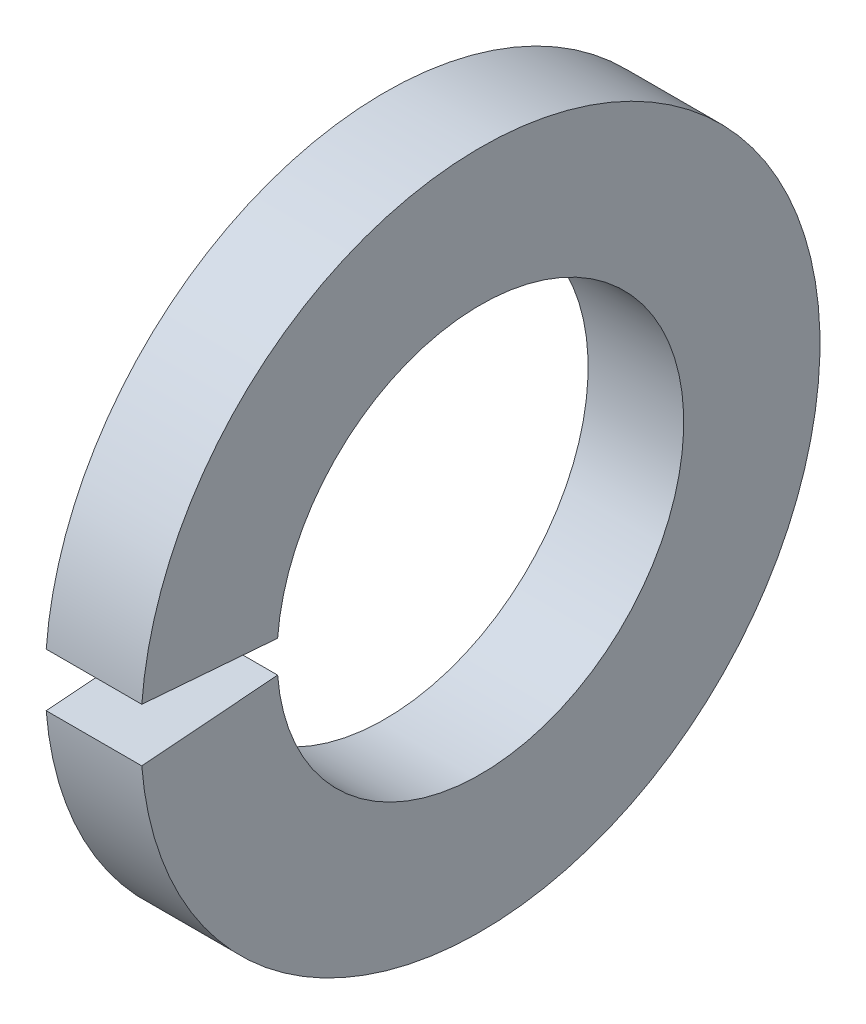
SolidWorks part; units mm, degrees
material "Chrome Stainless Steel"
ref_plane "Front Plane" through (0, 0, 0) normal (0, 0, 1) x (1, 0, 0)
ref_plane "Top Plane" through (0, 0, 0) normal (0, 1, 0) x (1, 0, 0)
ref_plane "Right Plane" through (0, 0, 0) normal (1, 0, 0) x (0, 0, -1)
ref_plane "Plane1" through (0, 0, 0) normal (0, 0.9969, 0.0785) x (-1, 0, 0)
sketch "Sketch1" plane through (0, 0, 0) normal (0, 0.9969, 0.0785) x (-1, 0, 0)
  line L0 (1.1938, 4.2418) -> (0, 4.2418)
  line L1 (0, 4.2418) -> (0, 2.54)
  line L2 (0, 2.54) -> (1.1938, 2.54)
  line L3 (1.1938, 2.54) -> (1.1938, 4.2418)
  line L4 (0, 0) -> (1.1938, 0) construction
revolve "Revolve1" add sketch "Sketch1" angle 351 about L4
